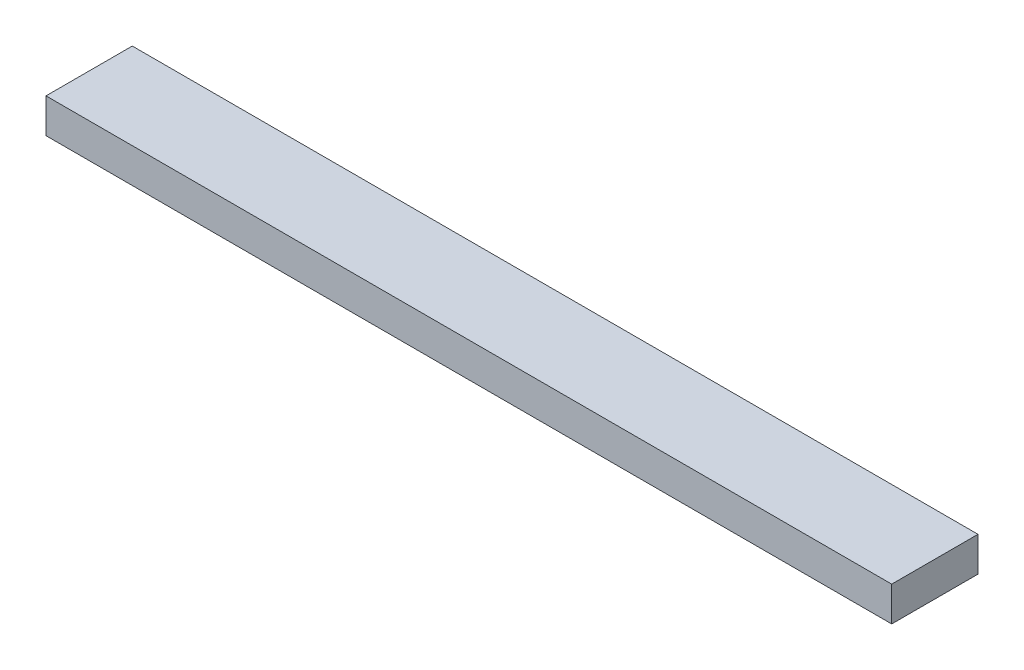
SolidWorks part; units mm, degrees
material "Perspex (TM) GS Acrylic Cast Sheet"
ref_plane "Front Plane" through (0, 0, 0) normal (0, 0, 1) x (1, 0, 0)
ref_plane "Top Plane" through (0, 0, 0) normal (0, 1, 0) x (1, 0, 0)
ref_plane "Right Plane" through (0, 0, 0) normal (1, 0, 0) x (0, 0, -1)
sketch "Sketch1" plane through (0, 0, 0) normal (0, 1, 0) x (1, 0, 0)
  line L1 (0, 0) -> (98, 0)
  line L2 (0, 0) -> (0, 10)
  line L3 (0, 10) -> (98, 10)
  line L4 (98, 0) -> (98, 10)
  dimension "D1" = 98
  dimension "D2" = 10
extrude "Boss-Extrude1" add sketch "Sketch1" along normal blind 4
